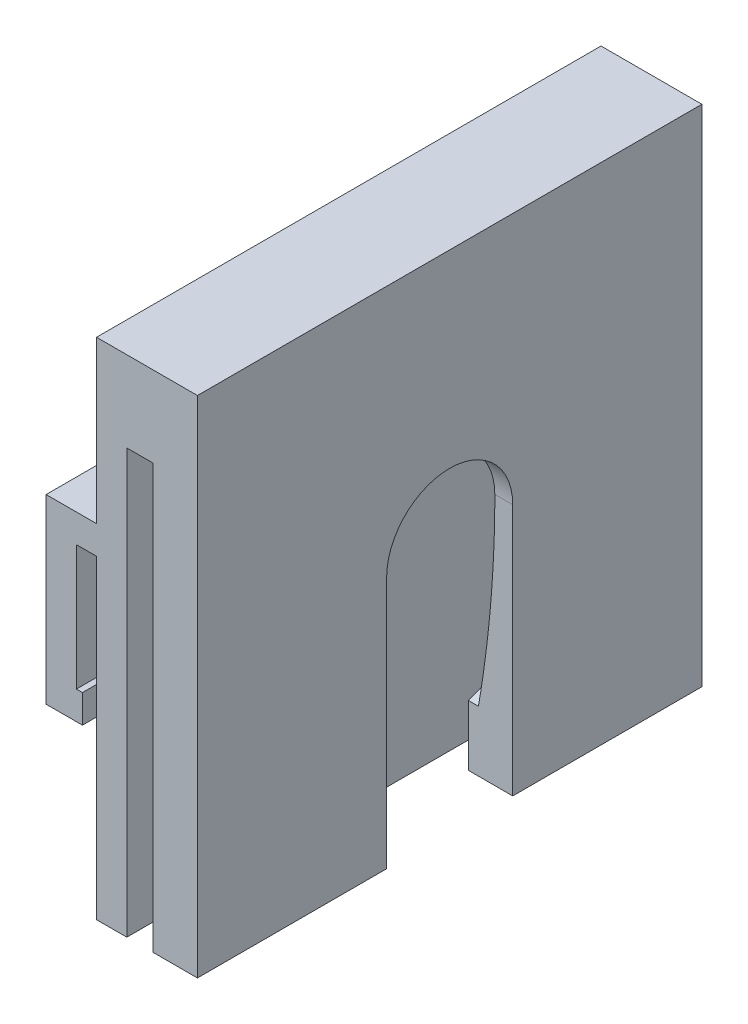
SolidWorks part; units mm, degrees
ref_plane "Plan de face" through (0, 0, 0) normal (0, 0, 1) x (1, 0, 0)
ref_plane "Plan de dessus" through (0, 0, 0) normal (0, 1, 0) x (1, 0, 0)
ref_plane "Plan de droite" through (0, 0, 0) normal (1, 0, 0) x (0, 0, -1)
sketch "Sketch1" plane through (0, 0, 0) normal (0, 0, 1) x (1, 0, 0)
  line L1 (2, 4.5) -> (-2, 4.5)
  line L2 (2, 4.5) -> (2, -4.5)
  line L3 (2, -4.5) -> (-2, -4.5)
  line L4 (-2, 4.5) -> (-2, -4.5)
  line L5 (2, 4.5) -> (-2, -4.5) construction
  line L6 (2, -4.5) -> (-2, 4.5) construction
  point P0 (0, 0)
  dimension "D1" = 9
  dimension "D2" = 4
extrude "Boss-Extrude1" add sketch "Sketch1" along normal blind 25
sketch "Sketch2" plane through (0, 0, 0) normal (0, 0, -1) x (-1, 0, 0)
  line L1 (0.5, 3) -> (-0.5, 3)
  line L2 (0.5, 3) -> (0.5, -3)
  line L3 (0.5, -3) -> (-0.5, -3)
  line L4 (-0.5, 3) -> (-0.5, -3)
  line L5 (0.5, 3) -> (-0.5, -3) construction
  line L6 (0.5, -3) -> (-0.5, 3) construction
  point P0 (0, 0)
  dimension "D1" = 1
  dimension "D2" = 6
extrude "Cut-Extrude1" cut sketch "Sketch2" against normal through all
sketch "Sketch4" plane through (2, 0, 0) normal (1, 0, 0) x (0, 0, -1)
  line L0 (-25, -4.5) -> (-25, 4.5) construction
  line L1 (-25, 12.5) -> (0, 12.5)
  line L2 (-25, 12.5) -> (-25, -12.5)
  line L3 (-25, -12.5) -> (0, -12.5)
  line L4 (0, 12.5) -> (0, -12.5)
  line L5 (0, -4.5) -> (0, 4.5) construction
  line L6 (-25, 12.5) -> (0, 4.5) construction
  line L7 (0, -4.5) -> (-25, -12.5) construction
extrude "Boss-Extrude2" add sketch "Sketch4" against normal up to surface (1.5 mm away) up to face at (0.5, 0, 12.5)
ref_plane "Plane1" through (2, 0, 0) normal (1, 0, 0) x (0, 0, -1)
ref_plane "Plane2" through (0, 0, 12.5) normal (0, 0, -1) x (-1, 0, 0)
ref_plane "Plane3" through (0, 0, 0) normal (0, 1, 0) x (1, 0, 0)
ref_axis "Axis1" through (2.075, 0, 12.5) along (-1, 0, 0)
sketch "Sketch5" plane through (2, 0, 0) normal (1, 0, 0) x (0, 0, -1)
  line L4 (0, -12.5) -> (0, 12.5)
  line L5 (0, -12.5) -> (0, 12.5)
  line L6 (0, 12.5) -> (-25, 12.5)
  line L7 (0, 12.5) -> (-25, 12.5)
  line L8 (-25, 12.5) -> (-25, -12.5)
  line L9 (-25, 12.5) -> (-25, -12.5)
  line L10 (-25, -12.5) -> (0, -12.5)
  line L11 (-25, -12.5) -> (0, -12.5)
  dimension "D1" = 0
extrude "Boss-Extrude3" add sketch "Sketch5" along normal blind 3.5
sketch "Sketch6" plane through (0, 0, 12.5) normal (0, 0, -1) x (-1, 0, 0)
  line L0 (-2, 10) -> (-2, 0)
  line L1 (-2, 55) -> (-2, -55) construction
  line L2 (-2, 10) -> (-3.8, 10)
  line L3 (-3.8, 10) -> (-3.8, 0) construction
  line L4 (2.75, 0) -> (-2.75, 0) construction
  line L5 (-5.5, 12.5) -> (-5.5, -12.5) construction
  line L6 (-5.5, 12.5) -> (-5.5, -12.5) construction
  line L7 (-5.5, 12.5) -> (-3.8, 10) construction
  line L9 (-2, 0) -> (-4.6999, 0)
  arc A0 (-3.8, 10) -> (-4.6999, 0) centre (51.31, 0) ccw
  dimension "D3" = 55.11
  dimension "D1" = 1.8
  dimension "D2" = 10
revolve "Cut-Revolve2" cut sketch "Sketch6" angle 360 about axis through (2.075, 0, 12.5) along (-1, 0, 0)
sketch "Sketch7" plane through (0, -12.5, 0) normal (0, -1, 0) x (1, 0, 0)
  line L0 (0.5, 25) -> (5.5, 25) construction
  line L1 (2, 25) -> (3.8, 25)
  line L2 (2, 25) -> (2, 0)
  line L3 (2, 0) -> (3.8, 0)
  line L4 (3.8, 25) -> (3.8, 0)
  line L5 (0.5, 0) -> (5.5, 0) construction
  line L6 (2, 2.5) -> (2, 22.5) construction
  line L7 (3.8, 2.5) -> (3.8, 22.5) construction
extrude "Cut-Extrude5" cut sketch "Sketch7" against normal blind 21
sketch "Sketch8" plane through (5.5, 0, 0) normal (1, 0, 0) x (0, 0, -1)
  line L0 (-12.5, 0) -> (-12.5, -12.5) construction
  line L1 (-9.375, 0) -> (-9.375, -12.5)
  line L2 (-15.625, 0) -> (-15.625, -12.5)
  line L3 (-12.5, -4.125) -> (-12.5, 4.125) construction
  line L4 (2.75, 0) -> (-2.75, 0) construction
  line L5 (-25, -12.5) -> (0, -12.5) construction
  arc A0 (-9.375, 0) -> (-15.625, 0) centre (-12.5, 0) ccw
  arc A1 (-15.625, -12.5) -> (-9.375, -12.5) centre (-12.5, -12.5) ccw
  point P2 (-12.5, -6.25)
  dimension "D1" = 6.25
extrude "Cut-Extrude6" cut sketch "Sketch8" against normal up to surface (1.7 mm away)
sketch "Sketch9" plane through (3.8, 0, 0) normal (-1, 0, 0) x (0, 0, 1)
  line L0 (15.625, -9.4992) -> (15.625, -12.5) construction
  line L1 (15.625, -12.5) -> (25, -12.5) construction
  line L2 (25, -12.5) -> (25, 8.5) construction
  line L3 (25, 8.5) -> (17.7678, 8.5) construction
  line L4 (0, -12.5) -> (9.375, -12.5) construction
  line L5 (9.375, -12.5) -> (9.375, -9.4992) construction
  line L6 (7.2322, 8.5) -> (0, 8.5) construction
  line L7 (0, 8.5) -> (0, -12.5) construction
  line L8 (15.625, -9.4992) -> (15.625, -12.5)
  line L9 (15.625, -12.5) -> (25, -12.5)
  line L10 (25, -12.5) -> (25, 8.5)
  line L11 (25, 8.5) -> (17.7678, 8.5)
  line L12 (0, -12.5) -> (9.375, -12.5)
  line L13 (9.375, -12.5) -> (9.375, -9.4992)
  line L14 (7.2322, 8.5) -> (0, 8.5)
  line L15 (0, 8.5) -> (0, -12.5)
  arc A0 (15.625, -9.4992) -> (17.7678, 8.5) centre (12.5, 0) ccw construction
  arc A1 (7.2322, 8.5) -> (9.375, -9.4992) centre (12.5, 0) ccw construction
  arc A2 (15.625, -9.4992) -> (17.7678, 8.5) centre (12.5, 0) ccw
  arc A3 (7.2322, 8.5) -> (9.375, -9.4992) centre (12.5, 0) ccw
extrude "Boss-Extrude4" add sketch "Sketch9" along normal blind 0.5
sketch "Sketch11" plane through (0, 0, 0) normal (0, 0, -1) x (-1, 0, 0)
  line L0 (-0.5, -4.5) -> (-0.5, -12.5) construction
  line L1 (-0.5, -4.5) -> (0.2, -4.5)
  line L2 (-0.5, -4.5) -> (-0.5, -3)
  line L3 (-0.5, -3) -> (0.2, -3)
  line L4 (0.2, -4.5) -> (0.2, -3)
  line L5 (2, -4.5) -> (-0.5, -4.5) construction
  line L6 (-0.5, -3) -> (0.5, -3) construction
  line L7 (0.5, -3) -> (0.5, 3) construction
  dimension "D1" = 0.3
extrude "Cut-Extrude7" cut sketch "Sketch11" against normal through all
sketch "Sketch12" plane through (0, 0, 0) normal (0, 0, -1) x (-1, 0, 0)
  line L0 (0.5, -3) -> (0.5, 3) construction
  line L1 (-0.5, 3.1) -> (0.5, 3.1)
  line L2 (-0.5, 3.1) -> (-0.5, -3.1)
  line L3 (-0.5, -3.1) -> (0.5, -3.1)
  line L4 (0.5, 3.1) -> (0.5, -3.1)
  line L5 (-0.5, 3) -> (-0.5, -12.5) construction
  line L6 (0.5, 3.1) -> (2, 4.5) construction
  line L7 (0.5, -3.1) -> (2, -4.5) construction
  line L9 (0.5, 3) -> (-0.5, 3) construction
  dimension "D1" = 0.1
extrude "Cut-Extrude8" cut sketch "Sketch12" against normal through all
